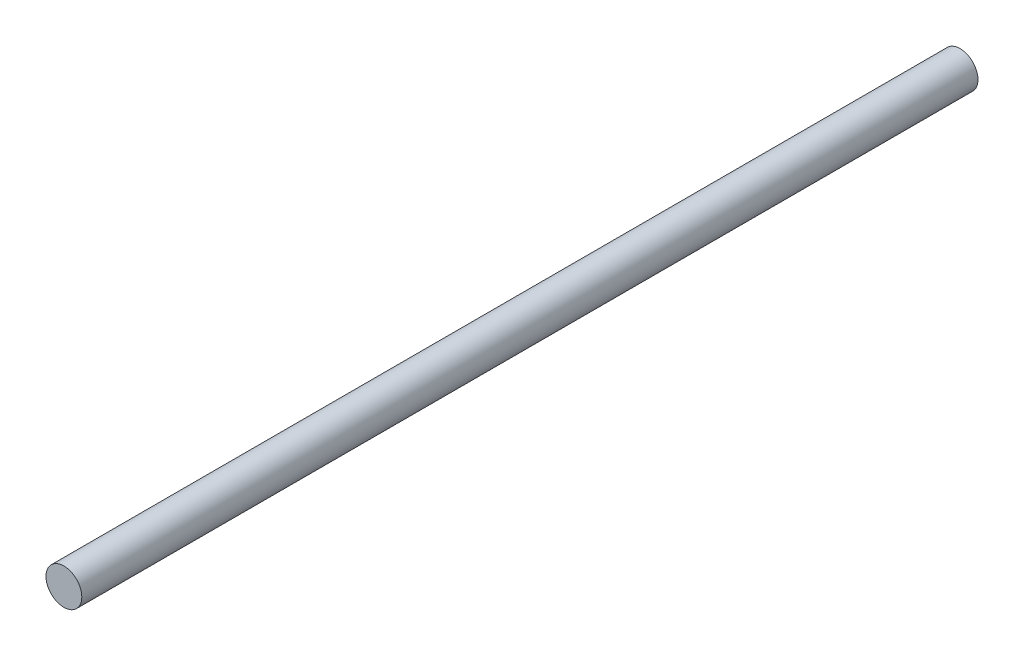
SolidWorks part; units mm, degrees
ref_plane "Front Plane" through (0, 0, 0) normal (0, 0, 1) x (1, 0, 0)
ref_plane "Top Plane" through (0, 0, 0) normal (0, 1, 0) x (1, 0, 0)
ref_plane "Right Plane" through (0, 0, 0) normal (1, 0, 0) x (0, 0, -1)
sketch "Sketch1" plane through (0, 0, 0) normal (0, 0, 1) x (1, 0, 0)
  circle A0 centre (0, 0) radius 4
  dimension "D1" = 8
extrude "Boss-Extrude1" add sketch "Sketch1" along normal mid plane 200
